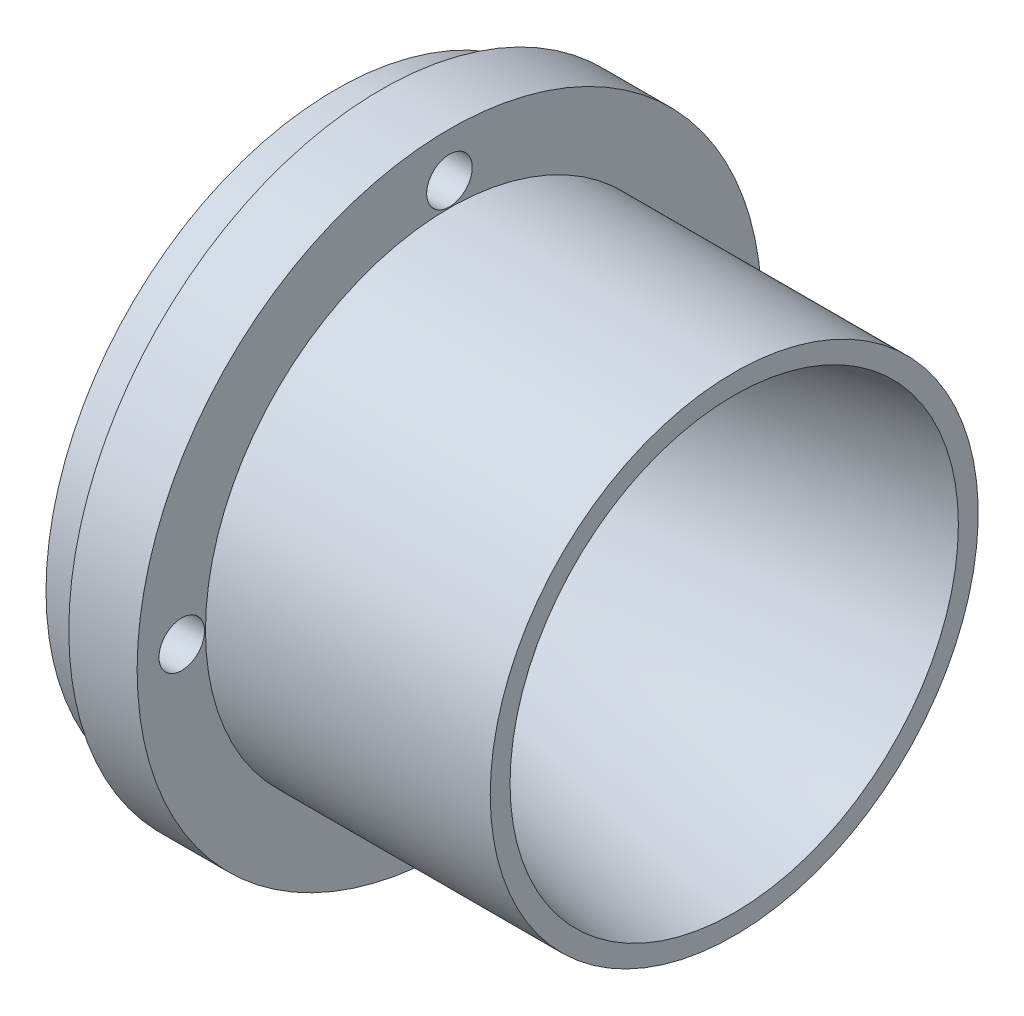
SolidWorks part; units mm, degrees
material "AISI 304"
ref_plane "Front Plane" through (0, 0, 0) normal (0, 0, 1) x (1, 0, 0)
ref_plane "Top Plane" through (0, 0, 0) normal (0, 1, 0) x (1, 0, 0)
ref_plane "Right Plane" through (0, 0, 0) normal (1, 0, 0) x (0, 0, -1)
ref_axis "Axis1" through (-14.407, 0, 0) along (1, 0, 0)
sketch "Sketch1" plane through (0, 0, 0) normal (0, 0, 1) x (1, 0, 0)
  line L0 (0, -55) -> (0, 55) construction
  line L1 (0, 34.8234) -> (101.6, 34.8234)
  line L2 (0, 34.8234) -> (0, 0)
  line L3 (0, 0) -> (101.6, 0)
  line L4 (101.6, 34.8234) -> (101.6, 0)
  line L5 (55, 0) -> (-55, 0) construction
  dimension "D1" = 34.8234
  dimension "D2" = 101.6
revolve "Revolve1" add sketch "Sketch1" angle 360 about axis through (-14.407, 0, 0) along (1, 0, 0)
sketch "Sketch2" plane through (0, 0, 0) normal (0, 0, 1) x (1, 0, 0)
  line L0 (0, 28.4734) -> (10.16, 28.4734)
  line L1 (0, -38.3057) -> (0, 38.3057) construction
  line L2 (0, 28.4734) -> (0, 0)
  line L3 (101.6, 24.9936) -> (101.6, 0)
  line L5 (101.6, -34.8234) -> (101.6, 34.8234) construction
  line L7 (101.6, 0) -> (0, 0)
  line L8 (48.1206, 8.8004) -> (59.2205, 13.9763) construction
  line L9 (101.6, 24.9936) -> (122.8287, 29.12) construction
  arc A0 (10.16, 28.4734) -> (36.83, 14.151) centre (10.16, -3.5192) cw
  arc A1 (36.83, 14.151) -> (46.482, 8.5) centre (47.4171, 21.1655) ccw
  arc A2 (46.482, 8.5) -> (48.1206, 8.8004) centre (46.7251, 11.793) ccw
  arc A3 (48.1206, 8.8004) -> (101.6, 24.9936) centre (131.3678, -169.7237) cw
  parabola Q0 (101.6, 24.9936) -> (48.1206, 8.8004) focus (30.6468, -36.2749) apex (8.7156, -28.8042) construction
  dimension "D3" = 3.302
  dimension "D4" = 12.7
  dimension "D1" = 28.4734
  dimension "D2" = 10.16
  dimension "D5" = 25
  dimension "D6" = 26.67
  dimension "D7" = 8.5
  dimension "D8" = 11
  dimension "D9" = 46.482
  dimension "D10" = 24.9936
revolve "Cut-Revolve1" cut sketch "Sketch2" angle 360 about axis through (-14.407, 0, 0) along (1, 0, 0)
sketch "Sketch3" plane through (0, 0, 0) normal (0, 0, 1) x (1, 0, 0)
  line L0 (0, -38.3057) -> (0, 38.3057) construction
  line L1 (0, 34.8234) -> (6.35, 34.8234)
  line L2 (0, 34.8234) -> (0, 32.1564)
  line L3 (0, 32.1564) -> (6.35, 32.1564)
  line L4 (6.35, 34.8234) -> (6.35, 32.1564)
  line L5 (-14.407, 0) -> (111.4249, 0) construction
  dimension "D1" = 6.35
  dimension "D2" = 32.1564
  dimension "D3" = 34.8234
revolve "Cut-Revolve2" cut sketch "Sketch3" angle 360 about axis through (-14.407, 0, 0) along (1, 0, 0)
sketch "Sketch4" plane through (0, 0, 0) normal (0, 0, 1) x (1, 0, 0)
  line L0 (101.6, -34.8234) -> (101.6, 34.8234) construction
  line L1 (101.6, 27.2034) -> (69.85, 27.2034)
  line L2 (101.6, 27.2034) -> (101.6, 34.8234)
  line L3 (101.6, 34.8234) -> (69.85, 34.8234)
  line L4 (69.85, 27.2034) -> (69.85, 34.8234)
  line L5 (-14.407, 0) -> (111.4249, 0) construction
  dimension "D1" = 7.62
  dimension "D2" = 31.75
  dimension "D3" = 34.8234
revolve "Cut-Revolve3" cut sketch "Sketch4" angle 360 about axis through (-14.407, 0, 0) along (1, 0, 0)
sketch "Sketch6" plane through (0, 0, 0) normal (0, 0, 1) x (1, 0, 0)
  line L0 (57.15, 0) -> (57.15, 32.2834)
  line L1 (38.3057, 0) -> (-38.3057, 0) construction
  line L2 (57.15, 32.2834) -> (62.23, 32.2834)
  line L3 (62.23, 32.2834) -> (62.23, 34.8234)
  line L4 (62.23, 34.8234) -> (0, 34.8234)
  line L5 (0, -38.3057) -> (0, 38.3057) construction
  line L6 (0, 34.8234) -> (0, 0)
  line L7 (0, 0) -> (57.15, 0)
  line L8 (-14.407, 0) -> (111.4249, 0) construction
  dimension "D1" = 34.8234
  dimension "D2" = 57.15
  dimension "D3" = 2.54
  dimension "D4" = 5.08
revolve "Cut-Revolve4" cut sketch "Sketch6" angle 360 about axis through (-14.407, 0, 0) along (1, 0, 0)
ref_plane "Plane1" through (62.23, 0, 0) normal (-1, 0, 0) x (0, 0, 1)
hole_wizard "Hole1" positions "Sketch8" profile "Sketch9" legacy end condition through all
sketch "Sketch8" plane through (69.85, 0, 0) normal (1, 0, 0) x (0, 0, -1)
  point P0 (0, 29.845)
  dimension "D1" = 29.845
sketch "Sketch9" plane through (69.85, 29.845, 0) normal (0, 1, 0) x (0, 0, -1)
  line L0 (0, 0) -> (0, 12.7)
  line L1 (0, 12.7) -> (1.632, 12.7)
  line L3 (1.632, 12.7) -> (1.632, 4.064)
  line L4 (1.632, 4.064) -> (2.54, 4.064)
  line L5 (2.54, 4.064) -> (2.54, 0)
  line L7 (2.54, 0) -> (0, 0)
  line L11 (0, -6.35) -> (0, 107.95) construction
  dimension "Thru Hole Dia." = 3.2639
  dimension "Thru Hole Depth" = 12.7
  dimension "C'Bore Dia." = 5.08
  dimension "C'Bore Depth" = 4.064
pattern_circular "CirPattern1" count 4 over 360 about axis through (0, 0, 0) along (1, 0, 0) of "Hole1"
sketch "Sketch10" plane through (0, 0, 0) normal (0, 0, 1) x (1, 0, 0)
  line L0 (57.15, 32.2834) -> (57.15, -32.2834) construction
  line L1 (57.15, 19.939) -> (59.0804, 19.939)
  line L2 (57.15, 19.939) -> (57.15, 16.8402)
  line L3 (57.15, 16.8402) -> (59.0804, 16.8402)
  line L4 (59.0804, 19.939) -> (59.0804, 16.8402)
  line L6 (-14.407, 0) -> (111.4249, 0) construction
  dimension "D1" = 1.9304
  dimension "D2" = 3.0988
  dimension "D3" = 16.8402
revolve "Cut-Revolve6" [suppressed] cut sketch "Sketch10" angle 360 about axis through (-14.407, 0, 0) along (1, 0, 0)
ref_plane "Plane2" through (69.85, 0, 0) normal (1, 0, 0) x (0, 0, -1)
sketch "Sketch11" plane through (69.85, 0, 0) normal (1, 0, 0) x (0, 0, -1)
  line L5 (-5.3606, 26.67) -> (5.3606, 26.67)
  line L6 (24.4475, 0) -> (-24.4475, 0) construction
  arc A1 (5.3606, 26.67) -> (-5.3606, 26.67) centre (0, 0) ccw
  circle A2 centre (0, 0) radius 27.2034 construction
  dimension "D1" = 26.67
extrude "Cut-Extrude2" [suppressed] cut sketch "Sketch11" along normal up to next
pattern_circular "CirPattern2" [suppressed] count 4 over 360 about axis through (-14.407, 0, 0) along (1, 0, 0)
sketch "Sketch12" plane through (0, 0, 0) normal (0, 0, 1) x (1, 0, 0)
  line L0 (57.15, 32.2834) -> (57.15, -32.2834) construction
  line L1 (57.15, 25.9842) -> (59.0804, 25.9842)
  line L2 (57.15, 25.9842) -> (57.15, 22.8854)
  line L3 (57.15, 22.8854) -> (59.0804, 22.8854)
  line L4 (59.0804, 25.9842) -> (59.0804, 22.8854)
  line L5 (-14.407, 0) -> (111.4249, 0) construction
  dimension "D1" = 1.9304
  dimension "D2" = 3.0988
  dimension "D3" = 22.8854
revolve "Cut-Revolve7" cut sketch "Sketch12" angle 360 about axis through (-14.407, 0, 0) along (1, 0, 0)
equation "\"throat_radius\"= 8.5mm"
equation "\"diverg_circle_rad\"= 0.382 * \"throat_radius\""
equation "\"converg_circle_rad\"= 1.5 * \"throat_radius\""
